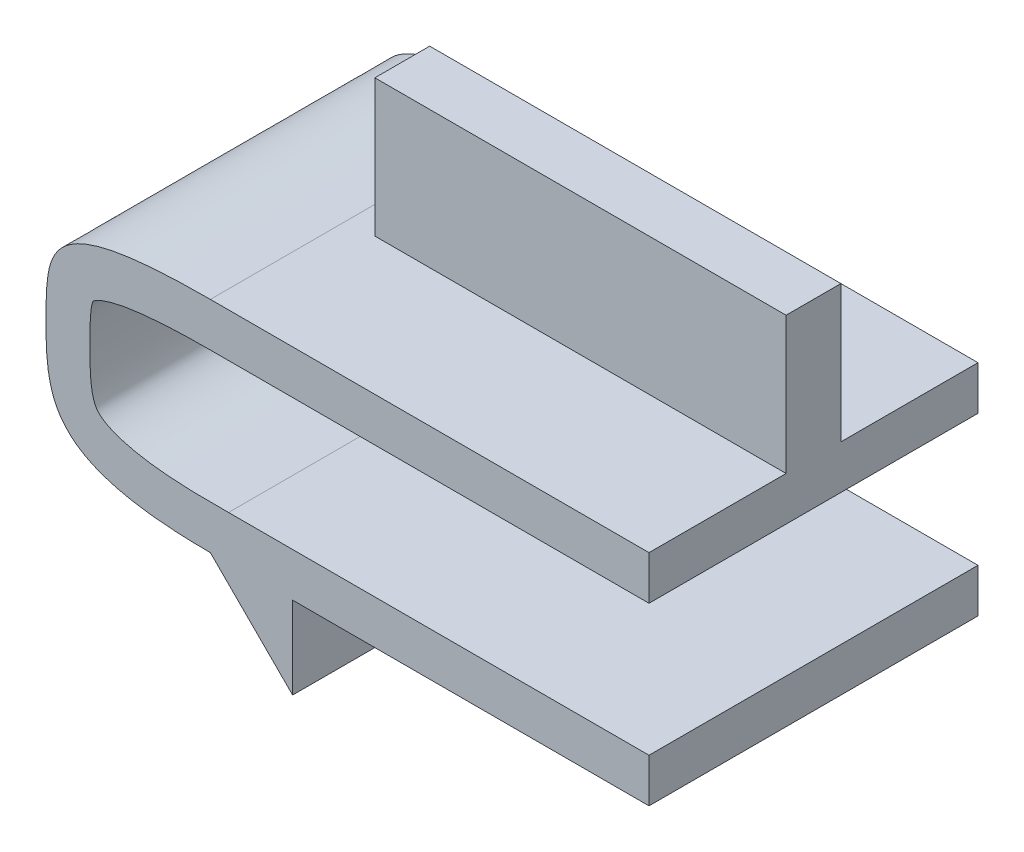
SolidWorks part; units mm, degrees
ref_plane "Front Plane" through (0, 0, 0) normal (0, 0, 1) x (1, 0, 0)
ref_plane "Top Plane" through (0, 0, 0) normal (0, 1, 0) x (1, 0, 0)
ref_plane "Right Plane" through (0, 0, 0) normal (1, 0, 0) x (0, 0, -1)
sketch "Sketch1" plane through (0, 0, 0) normal (1, 0, 0) x (0, 0, -1)
  line L1 (-61.2715, 49.1504) -> (-49.2715, 49.1504) construction
  line L2 (-61.2715, 49.1504) -> (-61.2715, 39.1504) construction
  line L3 (-61.2715, 39.1504) -> (-49.2715, 39.1504) construction
  line L4 (-49.2715, 49.1504) -> (-49.2715, 39.1504) construction
  dimension "D1" = 12
  dimension "D2" = 10
ref_plane "Plane1" through (0, 0, 61.2715) normal (0, 0, 1) x (1, 0, 0)
sketch "Sketch2" plane through (0, 0, 61.2715) normal (0, 0, 1) x (1, 0, 0)
  line L0 (0, 49.1504) -> (0, 39.1504) construction
  line L1 (0, 49.1504) -> (0, 39.1504) construction
  line L2 (0, 49.1504) -> (22, 49.1504) construction
  line L3 (22, 49.1504) -> (22, 39.1504) construction
  line L4 (22, 39.1504) -> (0, 39.1504) construction
  dimension "D1" = 22
sketch "Sketch3" plane through (0, 0, 61.2715) normal (0, 0, 1) x (1, 0, 0)
  line L0 (22, 49.1504) -> (6, 49.1504)
  line L1 (0, 49.1504) -> (0, 39.1504) construction
  line L2 (3.9935, 49.1504) -> (14.4894, 49.1504) construction
  line L3 (0, 42.4823) -> (0, 46.101) construction
  line L4 (13.3454, 41.1504) -> (4.5929, 41.1504) construction
  line L5 (22, 49.1504) -> (22, 39.1504) construction
  line L6 (22, 39.1504) -> (0, 39.1504) construction
  line L7 (6, 41.1504) -> (9, 38.1504)
  line L8 (9, 38.1504) -> (9, 41.1504)
  line L9 (9, 41.1504) -> (22, 41.1504)
  line L10 (22, 47.5504) -> (6, 47.5504)
  line L11 (7.4, 42.7504) -> (6.6627, 42.7504)
  line L13 (7.4, 42.7504) -> (22, 42.7504)
  line L14 (22, 49.1504) -> (22, 47.5504)
  line L15 (22, 42.7504) -> (22, 41.1504)
  line L16 (7.4, 42.0132) -> (7.4, 42.7504) construction
  line L17 (6.6627, 42.7504) -> (7.4, 42.0132) construction
  spline S0 degree 3 poles (6, 49.1504) (0.3979, 49.1504) (0.0006, 47.7793) (-0.0085, 43.1664) (0.5297, 41.1504) (6, 41.1504) knots 0 0 0 0 0.444599 0.544599 1 1 1 1
  spline S1 degree 1 poles (6, 47.5504) (6.6627, 42.7504) knots 0 0 1 1 construction
  spline S2 degree 3 poles (6, 47.5504) (5.8143, 47.5504) (5.4326, 47.5477) (4.7517, 47.5314) (3.9956, 47.4918) (3.2522, 47.4162) (2.4672, 47.2862) (1.8664, 47.0834) (1.7104, 46.9384) (1.7267, 46.9657) (1.6167, 46.6652) (1.5883, 45.5734) (1.6192, 44.5279) (1.6943, 43.9669) (1.8133, 43.6676) (1.934, 43.5048) (2.2792, 43.2526) (2.9765, 43.0136) (3.8197, 42.8669) (4.5999, 42.7881) (5.3761, 42.7532) (6.079, 42.7499) (6.4716, 42.7504) (6.6627, 42.7504) knots 0 0 0 0 0.015912 0.031825 0.063649 0.095474 0.127299 0.190948 0.254598 0.318247 0.381897 0.509195 0.572845 0.636494 0.700144 0.763793 0.827443 0.891092 0.922917 0.954742 0.986566 1.002479 1.018391 1.018391 1.018391 1.018391
  dimension "D1" = 6
  dimension "D2" = 3.6472
  dimension "D3" = 2
  dimension "D4" = 3
  dimension "D5" = 3
  dimension "D6" = 1.6
extrude "Boss-Extrude1" add sketch "Sketch3" against normal blind 12
sketch "Sketch4" plane through (0, 49.1504, 0) normal (0, 1, 0) x (1, 0, 0)
  line L0 (22, -55.2715) -> (7, -55.2715) construction
  line L1 (22, -49.2715) -> (22, -61.2715) construction
  line L3 (22, -54.2715) -> (7, -54.2715)
  line L4 (22, -54.2715) -> (22, -56.2715)
  line L5 (22, -56.2715) -> (7, -56.2715)
  line L6 (7, -54.2715) -> (7, -56.2715)
  line L7 (22, -54.2715) -> (7, -56.2715) construction
  line L8 (22, -56.2715) -> (7, -54.2715) construction
  point P4 (14.5, -55.2715)
  dimension "D1" = 15
  dimension "D2" = 2
extrude "Boss-Extrude2" add sketch "Sketch4" along normal blind 5
